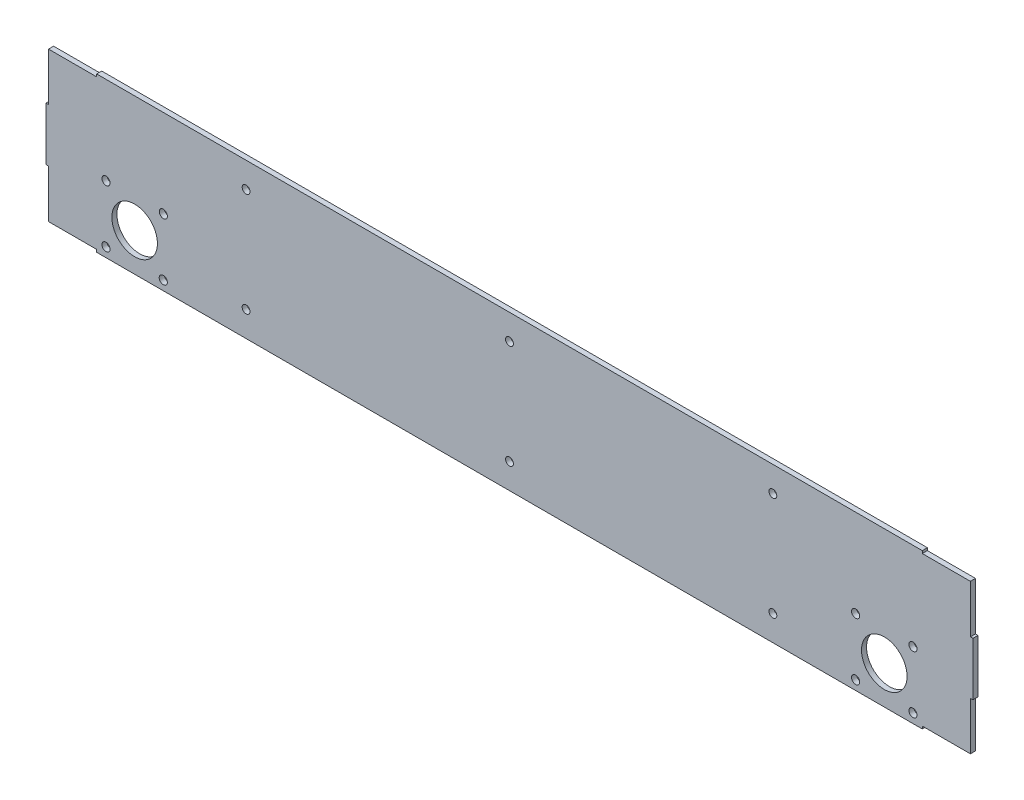
SolidWorks part; units mm, degrees
material "ABS PC"
ref_plane "Front Plane" through (0, 0, 0) normal (0, 0, 1) x (1, 0, 0)
ref_plane "Top Plane" through (0, 0, 0) normal (0, 1, 0) x (1, 0, 0)
ref_plane "Right Plane" through (0, 0, 0) normal (1, 0, 0) x (0, 0, -1)
sketch "Sketch2" plane through (0, 0, 0) normal (0, 0, 1) x (1, 0, 0)
  line L0 (0, 63.5) -> (-1.5875, 63.5)
  line L5 (-1.5875, 63.5) -> (-1.5875, 30.1625)
  line L6 (-1.5875, 30.1625) -> (0, 30.1625)
  line L7 (0, 93.6625) -> (0, 63.5)
  line L8 (0, 30.1625) -> (0, 0)
  line L9 (577.85, 93.6625) -> (577.85, 63.5)
  line L10 (577.85, 63.5) -> (579.4375, 63.5)
  line L11 (579.4375, 63.5) -> (579.4375, 30.1625)
  line L12 (579.4375, 30.1625) -> (577.85, 30.1625)
  line L13 (577.85, 30.1625) -> (577.85, 0)
  line L14 (0, 0) -> (30.1625, 0)
  line L15 (30.1625, 0) -> (30.1625, -1.5875)
  line L16 (30.1625, -1.5875) -> (547.6875, -1.5875)
  line L17 (547.6875, -1.5875) -> (547.6875, 0)
  line L18 (547.6875, 0) -> (577.85, 0)
  line L19 (577.85, 93.6625) -> (547.6875, 93.6625)
  line L20 (547.6875, 93.6625) -> (547.6875, 95.25)
  line L21 (547.6875, 95.25) -> (30.1625, 95.25)
  line L22 (30.1625, 95.25) -> (30.1625, 93.6625)
  line L23 (30.1625, 93.6625) -> (0, 93.6625)
  dimension "D2" = 577.85
  dimension "D3" = 1.5875
  dimension "D4" = 1.5875
  dimension "D5" = 1.5875
  dimension "D6" = 30.1625
  dimension "D7" = 30.1625
  dimension "D8" = 30.1625
  dimension "D9" = 30.1625
  dimension "D10" = 1.5875
  dimension "D11" = 1.5875
  dimension "D12" = 30.1625
  dimension "D13" = 1.5875
  dimension "D14" = 30.1625
  dimension "D15" = 1.5875
  dimension "D16" = 30.1625
  dimension "D17" = 95.25
  dimension "D18" = 30.1625
extrude "Boss-Extrude1" add sketch "Sketch2" along normal blind 3.175
hole_wizard "#10 (0.1935) Diameter Hole2" positions "Sketch3" profile "Sketch4" hole size "#10" standard "ANSI Inch" end condition through all
sketch "Sketch3" plane through (0, 0, 3.175) normal (0, 0, 1) x (1, 0, 0)
  line L6 (547.6875, 95.25) -> (30.1625, 95.25) construction
  line L8 (-1.5875, 46.8312) -> (579.4375, 46.8312) construction
  line L9 (-1.5875, 63.5) -> (-1.5875, 30.1625) construction
  line L10 (579.4375, 30.1625) -> (579.4375, 63.5) construction
  line L11 (288.925, 95.25) -> (288.925, -1.5875) construction
  line L12 (547.6875, 95.25) -> (30.1625, 95.25) construction
  line L13 (30.1625, -1.5875) -> (547.6875, -1.5875) construction
  point P16 (288.925, 79.375)
  point P18 (123.825, 79.375)
  point P20 (454.025, 79.375)
  point P53 (454.025, 14.2875)
  point P54 (123.825, 14.2875)
  point P55 (288.925, 14.2875)
  dimension "D1" = 15.875
  dimension "D2" = 15.875
  dimension "D3" = 15.875
  dimension "D4" = 165.1
  dimension "D5" = 165.1
  dimension "D6" = 0
sketch "Sketch4" plane through (288.925, 79.375, 3.175) normal (1, 0, 0) x (0, -1, 0)
  line L0 (0, 0) -> (0, 3.175)
  line L1 (0, 3.175) -> (2.4574, 3.175)
  line L2 (2.4574, 3.175) -> (2.4574, 0)
  line L5 (2.4574, 0) -> (0, 0)
  line L11 (0, -6.35) -> (0, 107.95) construction
  dimension "Thru Hole Dia." = 4.9149
  dimension "Thru Hole Depth" = 3.175
sketch "Sketch5" plane through (0, 0, 0) normal (0, 0, -1) x (-1, 0, 0)
  line L8 (-288.925, 95.25) -> (-288.925, -1.5875) construction
  line L9 (-547.6875, -1.5875) -> (-547.6875, 0) construction
  line L18 (-547.6875, 95.25) -> (-30.1625, 95.25) construction
  line L20 (-30.1625, -1.5875) -> (-547.6875, -1.5875) construction
  circle A5 centre (-541.8255, 40.1955) radius 2.5527
  circle A6 centre (-505.9245, 4.2545) radius 2.5527
  circle A7 centre (-523.875, 22.225) radius 14.2875
  circle A8 centre (-541.8455, 4.2745) radius 2.5527
  circle A9 centre (-505.9045, 40.1755) radius 2.5527
  circle A10 centre (-71.9455, 40.1755) radius 2.5527
  circle A11 centre (-36.0045, 4.2745) radius 2.5527
  circle A12 centre (-53.975, 22.225) radius 14.2875
  circle A13 centre (-71.9255, 4.2545) radius 2.5527
  circle A14 centre (-36.0245, 40.1955) radius 2.5527
  dimension "D5" = 28.575
  dimension "D3" = 35.921
  dimension "D7" = 35.921
  dimension "D8" = 25.4
  dimension "D9" = 25.4
  dimension "D10" = 25.4
  dimension "D11" = 5.862
  dimension "D6" = 35.921
  dimension "D2" = 5.842
  dimension "D4" = 35.921
  dimension "D12" = 5.842
extrude "Cut-Extrude2" cut sketch "Sketch5" against normal blind 6.35
